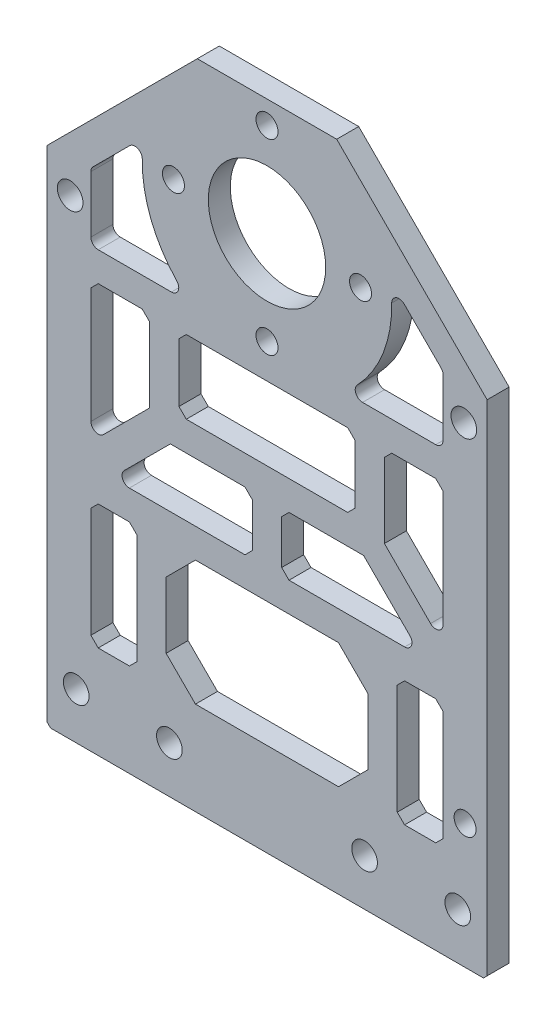
SolidWorks part; units mm, degrees
ref_plane "Plano frontal" through (0, 0, 0) normal (0, 0, 1) x (1, 0, 0)
ref_plane "Plano superior" through (0, 0, 0) normal (0, 1, 0) x (1, 0, 0)
ref_plane "Plano direito" through (0, 0, 0) normal (1, 0, 0) x (0, 0, -1)
sketch "Esboço1" plane through (0, 0, 0) normal (0, 0, 1) x (1, 0, 0)
  line L0 (0, 0) -> (0, 137)
  line L1 (0, 137) -> (41, 178)
  line L2 (41, 178) -> (79, 178)
  line L3 (79, 178) -> (120, 137)
  line L4 (120, 137) -> (120, 0)
  line L5 (120, 0) -> (0, 0)
  line L6 (60, 178) -> (60, 0) construction
  circle A0 centre (60, 146.25) radius 16
  dimension "D5" = 32
  dimension "D6" = 31.75
  dimension "D1" = 120
  dimension "D2" = 178
  dimension "D3" = 38
  dimension "D4" = 135
extrude "Ressalto-extrusão1" add sketch "Esboço1" along normal blind 6
sketch "Esboço2" plane through (0, 0, 0) normal (0, 0, -1) x (-1, 0, 0)
  line L0 (-60, 25.4) -> (-60, 0) construction
  line L1 (-87.5, 25.4) -> (-32.5, 25.4)
  line L2 (-87.5, 25.4) -> (-87.5, 59.4)
  line L3 (-87.5, 59.4) -> (-32.5, 59.4)
  line L4 (-32.5, 25.4) -> (-32.5, 59.4)
  line L5 (0, 0) -> (-120, 0) construction
  line L7 (-56, 83.4) -> (-28, 83.4)
  line L8 (-84, 111.4) -> (-36, 111.4)
  line L9 (-84, 111.4) -> (-84, 91.4)
  line L10 (-84, 91.4) -> (-36, 91.4)
  line L11 (-36, 111.4) -> (-36, 91.4)
  line L12 (-28, 83.4) -> (-28, 111.4)
  line L13 (-28, 111.4) -> (-12, 111.4)
  line L14 (-12, 111.4) -> (-12, 67.4)
  line L15 (-12, 25.4) -> (-24.5, 25.4)
  line L16 (-24.5, 25.4) -> (-24.5, 59.4)
  line L17 (-12, 67.4) -> (-56, 67.4)
  line L18 (-56, 67.4) -> (-56, 83.4)
  line L19 (-64, 83.4) -> (-64, 67.4)
  line L20 (-64, 67.4) -> (-108, 67.4)
  line L21 (-95.5, 59.4) -> (-95.5, 25.4)
  line L22 (-95.5, 25.4) -> (-108, 25.4)
  line L23 (-108, 25.4) -> (-108, 59.4)
  line L24 (-108, 111.4) -> (-92, 111.4)
  line L25 (-92, 111.4) -> (-92, 83.4)
  line L26 (-92, 83.4) -> (-64, 83.4)
  line L27 (-93.473, 152.2133) -> (-108, 137.6863)
  line L28 (-108, 137.6863) -> (-108, 119.4)
  line L29 (-108, 119.4) -> (-80.8585, 119.4)
  line L30 (-24.5, 59.4) -> (-12, 59.4)
  line L31 (-12, 59.4) -> (-12, 25.4)
  line L32 (-95.5, 59.4) -> (-108, 59.4)
  line L34 (-108, 67.4) -> (-108, 111.4)
  line L35 (-120, 0) -> (-120, 137) construction
  line L36 (0, 137) -> (0, 0) construction
  line L37 (0, 0) -> (-120, 0) construction
  line L38 (-120, 137) -> (-79, 178) construction
  line L39 (-26.527, 152.2133) -> (-12, 137.6863)
  line L40 (-12, 137.6863) -> (-12, 119.4)
  line L41 (-12, 119.4) -> (-39.1415, 119.4)
  circle A0 centre (-60, 146.25) radius 25.5 construction
  circle A1 centre (-60, 171.75) radius 3
  circle A2 centre (-34.5, 146.25) radius 3
  circle A3 centre (-60, 120.75) radius 3
  circle A4 centre (-85.5, 146.25) radius 3
  arc A5 (-80.8585, 119.4) -> (-93.473, 152.2133) centre (-60, 146.25) cw
  circle A6 centre (-60, 146.25) radius 16 construction
  arc A7 (-39.1415, 119.4) -> (-26.527, 152.2133) centre (-60, 146.25) ccw
  point P46 (-60, 146.25)
  dimension "D2" = 51
  dimension "D4" = 6
  dimension "D17" = 34
  dimension "D1" = 25.4
  dimension "D3" = 55
  dimension "D6" = 12
  dimension "D7" = 12
  dimension "D8" = 25.4
  dimension "D9" = 25.4
  dimension "D10" = 8
  dimension "D11" = 8
  dimension "D12" = 34
  dimension "D13" = 8
  dimension "D14" = 8
  dimension "D15" = 44
  dimension "D16" = 8
  dimension "D18" = 8
  dimension "D19" = 8
  dimension "D20" = 8
  dimension "D21" = 8
  dimension "D22" = 16
  dimension "D23" = 16
  dimension "D5" = 4
extrude "Corte-extrusão1" cut sketch "Esboço2" against normal through all
sketch "Esboço3" plane through (0, 0, 6) normal (0, 0, 1) x (1, 0, 0)
  line L0 (92, 83.4) -> (108, 67.4) construction
  line L1 (28, 83.4) -> (12, 67.4) construction
  line L2 (56, 67.4) -> (12, 67.4) construction
  line L3 (12, 67.4) -> (12, 111.4) construction
  line L4 (28, 89.0569) -> (12, 73.0569)
  line L5 (33.6569, 83.4) -> (17.6569, 67.4)
  line L6 (86.3431, 83.4) -> (102.3431, 67.4)
  line L7 (92, 89.0569) -> (108, 73.0569)
  line L8 (89.1716, 80.5716) -> (105.1716, 64.5716) construction
  line L9 (94.8284, 86.2284) -> (110.8284, 70.2284) construction
  line L10 (25.1716, 86.2284) -> (9.1716, 70.2284) construction
  line L11 (28, 111.4) -> (28, 83.4) construction
  line L12 (30.8284, 80.5716) -> (14.8284, 64.5716) construction
  line L13 (28, 83.4) -> (56, 83.4) construction
  line L14 (28, 89.0569) -> (28, 83.4)
  line L15 (28, 83.4) -> (33.6569, 83.4)
  line L16 (92, 83.4) -> (86.3431, 83.4)
  line L17 (64, 83.4) -> (92, 83.4) construction
  line L18 (92, 83.4) -> (92, 89.0569)
  line L19 (108, 67.4) -> (108, 73.0569)
  line L20 (108, 111.4) -> (108, 67.4) construction
  line L21 (108, 67.4) -> (102.3431, 67.4)
  line L22 (108, 67.4) -> (64, 67.4) construction
  line L23 (12, 67.4) -> (17.6569, 67.4)
  line L24 (12, 67.4) -> (12, 73.0569)
  dimension "D1" = 4
  dimension "D2" = 4
  dimension "D3" = 4
  dimension "D4" = 4
extrude "Ressalto-extrusão2" add sketch "Esboço3" against normal through all
sketch "Esboço4" plane through (0, 0, 6) normal (0, 0, 1) x (1, 0, 0)
  line L0 (0, 12.7) -> (120, 12.7) construction
  line L1 (0, 137) -> (0, 0) construction
  line L2 (120, 0) -> (120, 137) construction
  line L3 (0, 0) -> (120, 0) construction
  circle A0 centre (8, 12.7) radius 3.5
  circle A1 centre (33.4, 12.7) radius 3.5
  circle A2 centre (86.6, 12.7) radius 3.5
  circle A3 centre (112, 12.7) radius 3.5
  dimension "D3" = 8
  dimension "D4" = 7
  dimension "D1" = 12.7
  dimension "D2" = 25.4
  dimension "D5" = 8
  dimension "D6" = 25.4
extrude "Corte-extrusão2" cut sketch "Esboço4" against normal through all
fillet "Filete1" radius 2 12 edges at (108, 73.0569, 3) (12, 73.0569, 3) (102.3431, 67.4, 3) (17.6569, 67.4, 3) (39.1415, 119.4, 3) (12, 119.4, 3) (12, 137.6863, 3) (26.527, 152.2133, 3) (108, 137.6863, 3) (108, 119.4, 3) (80.8585, 119.4, 3) (93.473, 152.2133, 3)
chamfer "Chanfro1" distance 8 angle 45 4 edges at (87.5, 25.4, 3) (32.5, 25.4, 3) (87.5, 59.4, 3) (32.5, 59.4, 3)
chamfer "Chanfro2" distance 2 angle 45 20 edges at (95.5, 25.4, 3) (108, 25.4, 3) (24.5, 25.4, 3) (12, 25.4, 3) (12, 59.4, 3) (24.5, 59.4, 3) (108, 59.4, 3) (95.5, 59.4, 3) (56, 67.4, 3) (64, 67.4, 3) (56, 83.4, 3) (64, 83.4, 3) (108, 111.4, 3) (92, 111.4, 3) (36, 91.4, 3) (84, 91.4, 3) (84, 111.4, 3) (36, 111.4, 3) (28, 111.4, 3) (12, 111.4, 3)
sketch "Esboço5" plane through (0, 0, 6) normal (0, 0, 1) x (1, 0, 0)
  line L0 (0, 137) -> (0, 0) construction
  line L1 (60, 120.75) -> (60, 91.4) construction
  line L2 (82, 91.4) -> (38, 91.4) construction
  line L4 (33.9524, 119.4) -> (14, 119.4) construction
  circle A0 centre (6.35, 128.4) radius 3.5
  circle A1 centre (6.35, 128.4) radius 8 construction
  circle A2 centre (113.65, 128.4) radius 3.5
  dimension "D2" = 7
  dimension "D4" = 16
  dimension "D1" = 6.35
  dimension "D3" = 9
extrude "Corte-extrusão3" cut sketch "Esboço5" against normal through all
chamfer "Chanfro3" distance 1 angle 45 2 edges at (0, 0, 3) (120, 0, 3)
sketch "Esboço8" plane through (0, 0, 6) normal (0, 0, 1) x (1, 0, 0)
  line L0 (1, 0) -> (119, 0) construction
  line L1 (120, 1) -> (120, 137) construction
  circle A0 centre (114, 34) radius 3
  point P4 (114.5728, 34)
  dimension "D1" = 6
  dimension "D2" = 34
  dimension "D3" = 6
extrude "Corte-extrusão5" cut sketch "Esboço8" against normal through all
